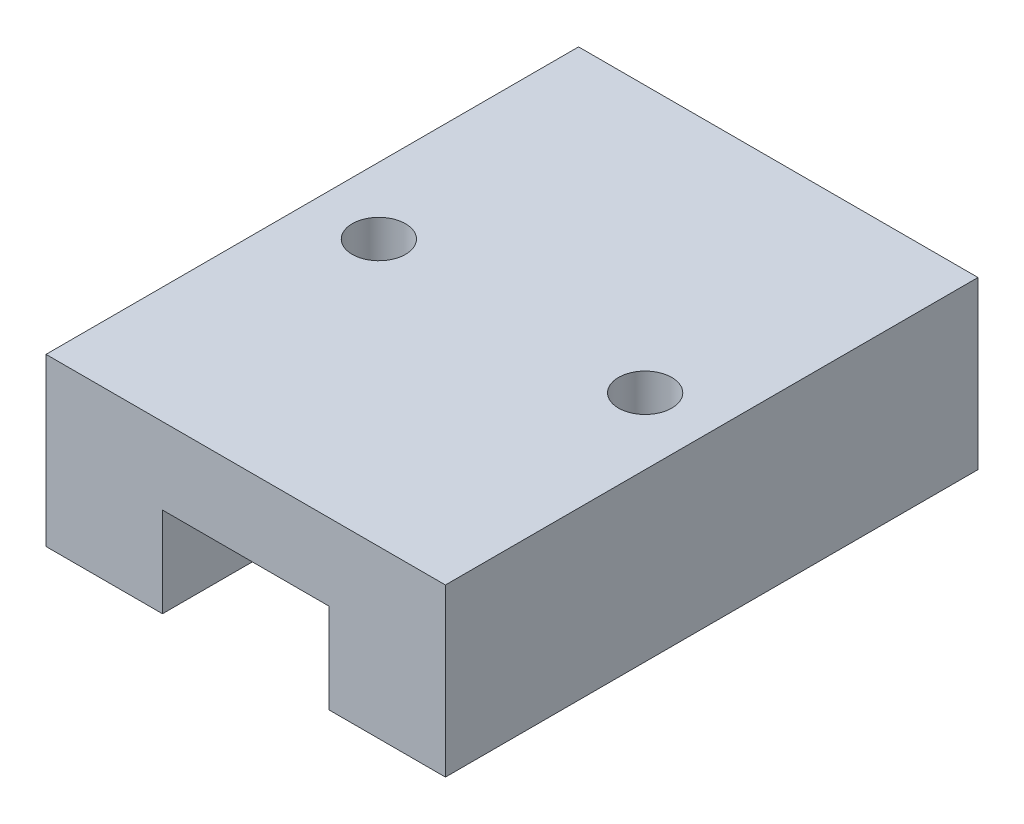
SolidWorks part; units mm, degrees
material "AISI 304"
ref_plane "前视基准面" through (0, 0, 0) normal (0, 0, 1) x (1, 0, 0)
ref_plane "上视基准面" through (0, 0, 0) normal (0, 1, 0) x (1, 0, 0)
ref_plane "右视基准面" through (0, 0, 0) normal (1, 0, 0) x (0, 0, -1)
other "Configuration Table"
sketch "草图1" plane through (0, 0, 0) normal (0, 0, 1) x (1, 0, 0)
  line L0 (0, 0) -> (0, 5) construction
  line L1 (-6, 5) -> (6, 5)
  line L2 (6, 5) -> (6, 0)
  line L3 (6, 0) -> (2.5, 0)
  line L4 (2.5, 0) -> (2.5, 2.7)
  line L5 (2.5, 2.7) -> (-2.5, 2.7)
  line L6 (-2.5, 0) -> (-2.5, 2.7)
  line L7 (-6, 0) -> (-2.5, 0)
  line L8 (-6, 5) -> (-6, 0)
  point P7 (0, 54.0434)
  point P10 (0, 2.7)
  dimension "D1" = 5
  dimension "D2" = 12
  dimension "D3" = 2.3
  dimension "D4" = 5
extrude "凸台-拉伸1" add sketch "草图1" along normal mid plane 16
sketch "草图2" plane through (0, 5, 0) normal (0, 1, 0) x (1, 0, 0)
  line L0 (-4, 0) -> (4, 0) construction
  point P4 (0, 0)
  dimension "D1" = 8
hole_wizard "M2 螺纹孔1" positions "草图3" profile "草图4" tap size "M2" standard "GB"
sketch "草图3" plane through (0, 5, 0) normal (0, 1, 0) x (1, 0, 0)
  point P0 (-4, 0)
  point P3 (4, 0)
sketch "草图4" plane through (-4, 5, 0) normal (1, 0, 0) x (0, 0, 1)
  line L0 (0, 0) -> (0, 3.1807)
  line L1 (0, 3.1807) -> (0.8, 2.7)
  line L2 (0.8, 2.7) -> (0.8, 0)
  line L5 (0.8, 0) -> (0, 0)
  line L10 (0, 3.1807) -> (-0.8, 2.7) construction
  line L11 (0, -6.35) -> (0, 107.95) construction
  dimension "螺纹孔钻头直径" = 1.6
  dimension "螺纹孔钻头深度" = 2.7
  dimension "导头角度" = 118
cosmetic thread "孔螺蚊线1"
cosmetic thread "孔螺蚊线2"
